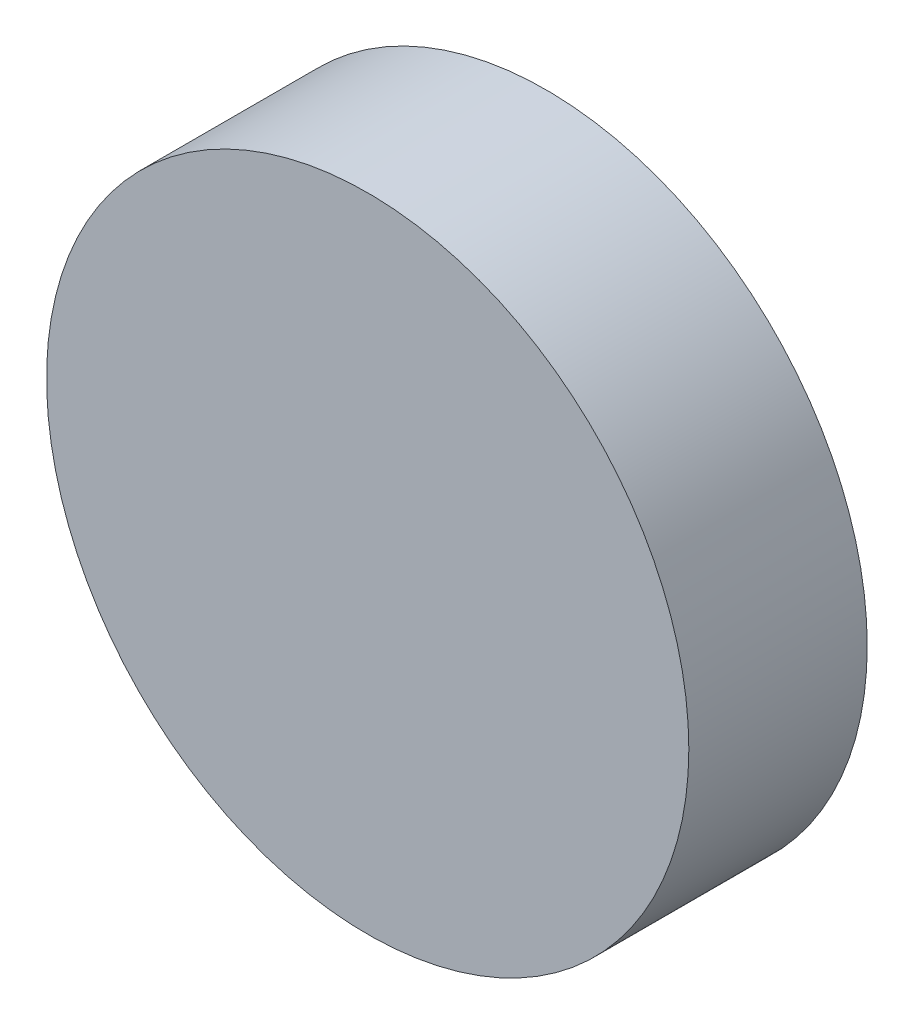
SolidWorks part; units mm, degrees
ref_plane "Front Plane" through (0, 0, 0) normal (0, 0, 1) x (1, 0, 0)
ref_plane "Top Plane" through (0, 0, 0) normal (0, 1, 0) x (1, 0, 0)
ref_plane "Right Plane" through (0, 0, 0) normal (1, 0, 0) x (0, 0, -1)
sketch "Sketch1" plane through (0, 0, 0) normal (0, 0, 1) x (1, 0, 0)
  circle A0 centre (40.506, 0.7624) radius 9
  dimension "D1" = 18
extrude "Boss-Extrude1" add sketch "Sketch1" along normal blind 5
